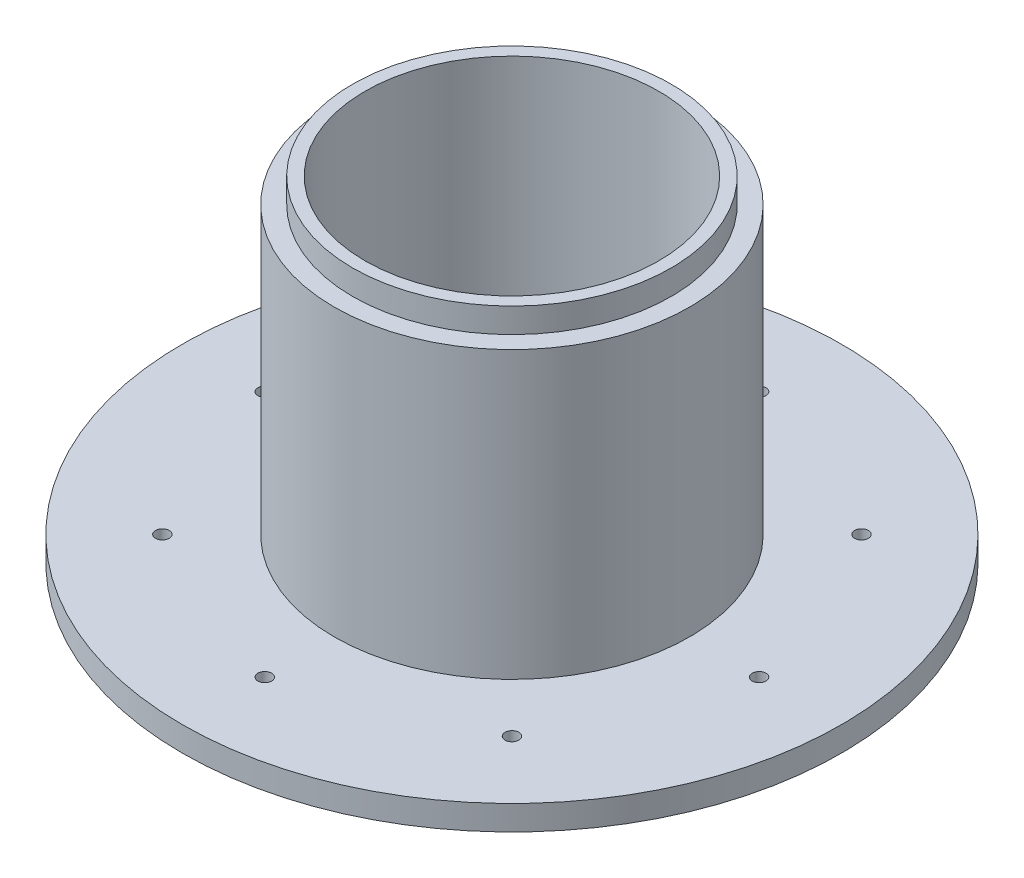
SolidWorks part; units mm, degrees
ref_plane "Front Plane" through (0, 0, 0) normal (0, 0, 1) x (1, 0, 0)
ref_plane "Top Plane" through (0, 0, 0) normal (0, 1, 0) x (1, 0, 0)
ref_plane "Right Plane" through (0, 0, 0) normal (1, 0, 0) x (0, 0, -1)
sketch "Sketch1" plane through (0, 0, 0) normal (0, 1, 0) x (1, 0, 0)
  circle A0 centre (0, 0) radius 60
  dimension "D1" = 120
extrude "Boss-Extrude1" add sketch "Sketch1" along normal blind 4.5
sketch "Sketch2" plane through (0, 4.5, 0) normal (0, 1, 0) x (1, 0, 0)
  circle A0 centre (0, 0) radius 29.275
  dimension "D1" = 58.55
extrude "Boss-Extrude2" add sketch "Sketch2" along normal blind 56.5
sketch "Sketch3" plane through (0, 61, 0) normal (0, 1, 0) x (1, 0, 0)
  circle A0 centre (0, 0) radius 26.75
  dimension "D1" = 53.5
extrude "Cut-Extrude1" cut sketch "Sketch3" against normal through all both and the other way through all
sketch "Sketch4" plane through (0, 4.5, 0) normal (0, 1, 0) x (1, 0, 0)
  circle A0 centre (0, 0) radius 32.3411
  circle A1 centre (0, 0) radius 29.275
extrude "Boss-Extrude3" add sketch "Sketch4" along normal up to surface (56.5 mm away) up to face at (0, 61, 26.75)
sketch "Sketch5" plane through (0, 61, 0) normal (0, 1, 0) x (1, 0, 0)
  circle A0 centre (0, 0) radius 29
  circle A1 centre (0, 0) radius 60 construction
  circle A2 centre (0, 0) radius 32.3411
  dimension "D1" = 31
extrude "Cut-Extrude2" cut sketch "Sketch5" against normal blind 4.5
sketch "Sketch6" plane through (0, 0, 0) normal (0, -1, 0) x (1, 0, 0)
  line L0 (0, 0) -> (60, 0) construction
  line L1 (0, 0) -> (-60, 0) construction
  line L2 (0, 0) -> (0, -60) construction
  line L3 (0, 0) -> (0, 60) construction
  line L4 (0, 0) -> (-42.4264, -42.4264) construction
  line L5 (0, 0) -> (42.4264, 42.4264) construction
  line L6 (0, 0) -> (42.4264, -42.4264) construction
  line L7 (0, 0) -> (-42.4264, 42.4264) construction
  circle A0 centre (0, 0) radius 60 construction
  circle A1 centre (31.8198, -31.8198) radius 1.25
  circle A2 centre (0, 45) radius 1.25
  circle A3 centre (31.8198, 31.8198) radius 1.25
  circle A4 centre (45, 0) radius 1.25
  circle A5 centre (-31.8198, 31.8198) radius 1.25
  circle A6 centre (-45, 0) radius 1.25
  circle A7 centre (-31.8198, -31.8198) radius 1.25
  circle A8 centre (0, -45) radius 1.25
  dimension "D1" = 2.5
  dimension "D2" = 45
  dimension "D3" = 45
  dimension "D4" = 45
  dimension "D5" = 45
  dimension "D6" = 45
  dimension "D7" = 45
  dimension "D8" = 45
  dimension "D9" = 45
extrude "Cut-Extrude3" cut sketch "Sketch6" against normal through all both and the other way through all
